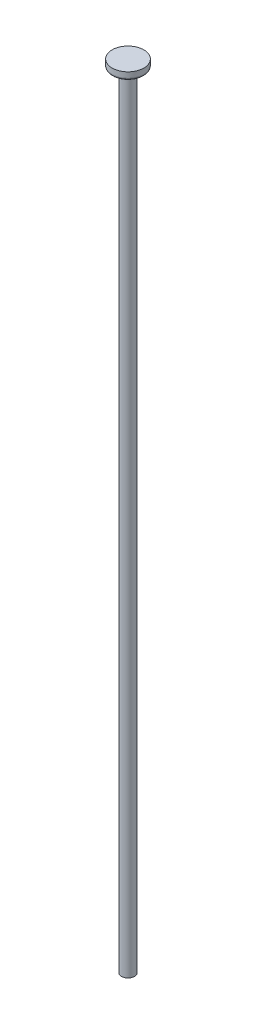
SolidWorks part; units mm, degrees
material "AISI 1020"
ref_plane "Front Plane" through (0, 0, 0) normal (0, 0, 1) x (1, 0, 0)
ref_plane "Top Plane" through (0, 0, 0) normal (0, 1, 0) x (1, 0, 0)
ref_plane "Right Plane" through (0, 0, 0) normal (1, 0, 0) x (0, 0, -1)
sketch "Sketch1" plane through (0, 0, 0) normal (0, 1, 0) x (1, 0, 0)
  circle A0 centre (0, 0) radius 0.889
  dimension "D1" = 1.778
extrude "Boss-Extrude1" add sketch "Sketch1" along normal blind 107.95
sketch "Sketch2" plane through (0, 107.95, 0) normal (0, 1, 0) x (1, 0, 0)
  circle A0 centre (0, 0) radius 2.159
  dimension "D1" = 4.318
extrude "Boss-Extrude2" add sketch "Sketch2" against normal blind 1.016
fillet "Fillet1" radius 0.254 1 edges at (0, 106.934, 2.159)
